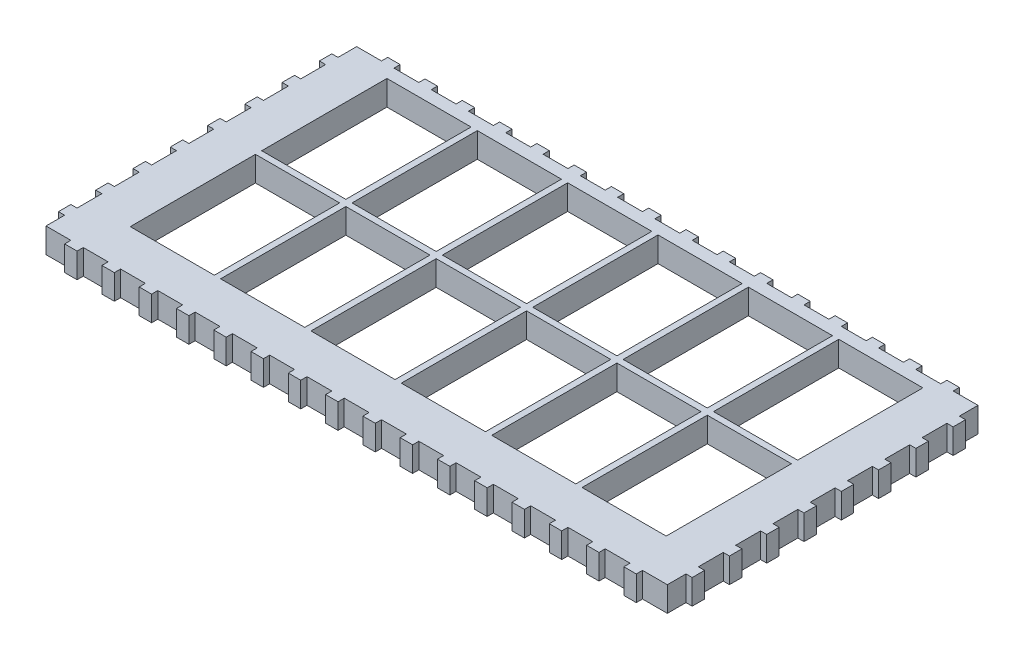
SolidWorks part; units mm, degrees
ref_plane "Front Plane" through (0, 0, 0) normal (0, 0, 1) x (1, 0, 0)
ref_plane "Top Plane" through (0, 0, 0) normal (0, 1, 0) x (1, 0, 0)
ref_plane "Right Plane" through (0, 0, 0) normal (1, 0, 0) x (0, 0, -1)
sketch "Sketch7" plane through (0, 0, 0) normal (0, 1, 0) x (1, 0, 0)
  line L0 (-95.525, 146.05) -> (-95.525, 18.05)
  line L1 (317.5, 158.75) -> (-317.5, 158.75)
  line L2 (317.5, 158.75) -> (317.5, -158.75)
  line L3 (317.5, -158.75) -> (-317.5, -158.75)
  line L4 (-317.5, 158.75) -> (-317.5, -158.75)
  line L5 (0, -158.75) -> (0, 158.75) construction
  line L6 (317.5, 0) -> (-317.5, 0) construction
  line L7 (-187.875, 146.05) -> (-273.875, 146.05)
  line L8 (-187.875, 146.05) -> (-187.875, 18.05)
  line L9 (-187.875, 18.05) -> (-273.875, 18.05)
  line L10 (-273.875, 146.05) -> (-273.875, 18.05)
  line L11 (-230.875, 18.05) -> (-230.875, 146.05) construction
  line L12 (-187.875, 82.05) -> (-273.875, 82.05) construction
  line L13 (-95.525, 18.05) -> (-181.525, 18.05)
  line L14 (-181.525, 146.05) -> (-181.525, 18.05)
  line L15 (-95.525, 146.05) -> (-181.525, 146.05)
  line L16 (-3.175, 146.05) -> (-3.175, 18.05)
  line L17 (-3.175, 18.05) -> (-89.175, 18.05)
  line L18 (-89.175, 146.05) -> (-89.175, 18.05)
  line L19 (-3.175, 146.05) -> (-89.175, 146.05)
  line L20 (89.175, 146.05) -> (89.175, 18.05)
  line L21 (89.175, 18.05) -> (3.175, 18.05)
  line L22 (3.175, 146.05) -> (3.175, 18.05)
  line L23 (89.175, 146.05) -> (3.175, 146.05)
  line L24 (181.525, 146.05) -> (181.525, 18.05)
  line L25 (181.525, 18.05) -> (95.525, 18.05)
  line L26 (95.525, 146.05) -> (95.525, 18.05)
  line L27 (181.525, 146.05) -> (95.525, 146.05)
  line L28 (273.875, 146.05) -> (273.875, 18.05)
  line L29 (273.875, 18.05) -> (187.875, 18.05)
  line L30 (187.875, 146.05) -> (187.875, 18.05)
  line L31 (273.875, 146.05) -> (187.875, 146.05)
  line L32 (-95.525, 11.7) -> (-95.525, -116.3)
  line L33 (-95.525, -116.3) -> (-181.525, -116.3)
  line L34 (-181.525, 11.7) -> (-181.525, -116.3)
  line L35 (-95.525, 11.7) -> (-181.525, 11.7)
  line L36 (-3.175, 11.7) -> (-3.175, -116.3)
  line L37 (-3.175, -116.3) -> (-89.175, -116.3)
  line L38 (-89.175, 11.7) -> (-89.175, -116.3)
  line L39 (-3.175, 11.7) -> (-89.175, 11.7)
  line L40 (89.175, 11.7) -> (89.175, -116.3)
  line L41 (89.175, -116.3) -> (3.175, -116.3)
  line L42 (3.175, 11.7) -> (3.175, -116.3)
  line L43 (89.175, 11.7) -> (3.175, 11.7)
  line L44 (181.525, 11.7) -> (181.525, -116.3)
  line L45 (181.525, -116.3) -> (95.525, -116.3)
  line L46 (95.525, 11.7) -> (95.525, -116.3)
  line L47 (181.525, 11.7) -> (95.525, 11.7)
  line L48 (273.875, 11.7) -> (273.875, -116.3)
  line L49 (273.875, -116.3) -> (187.875, -116.3)
  line L50 (187.875, 11.7) -> (187.875, -116.3)
  line L51 (273.875, 11.7) -> (187.875, 11.7)
  line L52 (-187.875, 11.7) -> (-187.875, -116.3)
  line L53 (-187.875, -116.3) -> (-273.875, -116.3)
  line L54 (-273.875, 11.7) -> (-273.875, -116.3)
  line L55 (-187.875, 11.7) -> (-273.875, 11.7)
  line L56 (-317.5, 146.05) -> (-273.875, 146.05) construction
  line L57 (273.875, 146.05) -> (317.5, 146.05) construction
  line L78 (-273.875, 146.05) -> (-317.5, 146.05) construction
  line L81 (-187.875, 18.05) -> (-187.875, 23.22) construction
  line L82 (-273.875, 146.05) -> (-273.875, 158.75) construction
  point P0 (0, 0)
  point P4 (-230.875, 82.05)
  dimension "D1" = 86
  dimension "D3" = 317.5
  dimension "D6" = 6.35
  dimension "D7" = 12.7
  dimension "D8" = 6.35
  dimension "D9" = 635
  dimension "D11" = 128
  dimension "D4" = 6
  dimension "D5" = 2
extrude "Boss-Extrude4" add sketch "Sketch7" along normal blind 25.4
sketch "Sketch8" plane through (0, 0, 0) normal (0, 1, 0) x (1, 0, 0)
  line L0 (-292.1, 158.75) -> (-292.1, 165.1)
  line L1 (-292.1, 165.1) -> (-279.4, 165.1)
  line L2 (-279.4, 165.1) -> (-279.4, 158.75)
  line L3 (317.5, 158.75) -> (-317.5, 158.75) construction
  line L4 (-292.1, 158.75) -> (-279.4, 158.75)
  line L29 (12.7, 165.1) -> (25.4, 165.1)
  line L58 (-317.5, 139.7) -> (-323.85, 139.7)
  line L59 (-317.5, 158.75) -> (-317.5, -158.75) construction
  line L60 (-323.85, 139.7) -> (-323.85, 127)
  line L61 (-323.85, 127) -> (-317.5, 127)
  line L62 (-317.5, 139.7) -> (-317.5, 127)
  line L63 (-323.85, 88.9) -> (-317.5, 88.9)
  line L64 (-317.5, 101.6) -> (-317.5, 88.9)
  line L65 (-317.5, 101.6) -> (-323.85, 101.6)
  line L66 (-323.85, 101.6) -> (-323.85, 88.9)
  line L67 (-323.85, 50.8) -> (-317.5, 50.8)
  line L68 (-317.5, 63.5) -> (-317.5, 50.8)
  line L69 (-317.5, 63.5) -> (-323.85, 63.5)
  line L70 (-323.85, 63.5) -> (-323.85, 50.8)
  line L71 (-323.85, 12.7) -> (-317.5, 12.7)
  line L72 (-317.5, 25.4) -> (-317.5, 12.7)
  line L73 (-317.5, 25.4) -> (-323.85, 25.4)
  line L74 (-323.85, 25.4) -> (-323.85, 12.7)
  line L75 (-323.85, -25.4) -> (-317.5, -25.4)
  line L76 (-317.5, -12.7) -> (-317.5, -25.4)
  line L77 (-317.5, -12.7) -> (-323.85, -12.7)
  line L78 (-323.85, -12.7) -> (-323.85, -25.4)
  line L95 (-323.85, -63.5) -> (-317.5, -63.5)
  line L120 (-317.5, -50.8) -> (-317.5, -63.5)
  line L121 (-317.5, -50.8) -> (-323.85, -50.8)
  line L122 (-323.85, -50.8) -> (-323.85, -63.5)
  line L123 (-323.85, -101.6) -> (-317.5, -101.6)
  line L124 (-317.5, -88.9) -> (-317.5, -101.6)
  line L125 (-317.5, -88.9) -> (-323.85, -88.9)
  line L126 (-323.85, -88.9) -> (-323.85, -101.6)
  line L127 (-323.85, -139.7) -> (-317.5, -139.7)
  line L128 (-317.5, -127) -> (-317.5, -139.7)
  line L129 (-317.5, -127) -> (-323.85, -127)
  line L130 (-323.85, -127) -> (-323.85, -139.7)
  line L131 (-317.5, -158.75) -> (317.5, -158.75) construction
  line L132 (-254, 165.1) -> (-241.3, 165.1)
  line L133 (-241.3, 165.1) -> (-241.3, 158.75)
  line L134 (-254, 158.75) -> (-241.3, 158.75)
  line L135 (-254, 158.75) -> (-254, 165.1)
  line L136 (-215.9, 165.1) -> (-203.2, 165.1)
  line L137 (-203.2, 165.1) -> (-203.2, 158.75)
  line L138 (-215.9, 158.75) -> (-203.2, 158.75)
  line L139 (-215.9, 158.75) -> (-215.9, 165.1)
  line L140 (-177.8, 165.1) -> (-165.1, 165.1)
  line L141 (-165.1, 165.1) -> (-165.1, 158.75)
  line L142 (-177.8, 158.75) -> (-165.1, 158.75)
  line L143 (-177.8, 158.75) -> (-177.8, 165.1)
  line L144 (-139.7, 165.1) -> (-127, 165.1)
  line L145 (-127, 165.1) -> (-127, 158.75)
  line L146 (-139.7, 158.75) -> (-127, 158.75)
  line L147 (-139.7, 158.75) -> (-139.7, 165.1)
  line L148 (-101.6, 165.1) -> (-88.9, 165.1)
  line L149 (-88.9, 165.1) -> (-88.9, 158.75)
  line L150 (-101.6, 158.75) -> (-88.9, 158.75)
  line L151 (-101.6, 158.75) -> (-101.6, 165.1)
  line L152 (-63.5, 165.1) -> (-50.8, 165.1)
  line L153 (-50.8, 165.1) -> (-50.8, 158.75)
  line L154 (-63.5, 158.75) -> (-50.8, 158.75)
  line L155 (-63.5, 158.75) -> (-63.5, 165.1)
  line L156 (-25.4, 165.1) -> (-12.7, 165.1)
  line L157 (-12.7, 165.1) -> (-12.7, 158.75)
  line L158 (-25.4, 158.75) -> (-12.7, 158.75)
  line L159 (-25.4, 158.75) -> (-25.4, 165.1)
  line L160 (-44.45, 139.7) -> (-50.8, 139.7) [skipped]
  line L161 (-50.8, 139.7) -> (-50.8, 127) [skipped]
  line L162 (-50.8, 127) -> (-44.45, 127) [skipped]
  line L163 (-44.45, 139.7) -> (-44.45, 127) [skipped]
  line L164 (-50.8, 88.9) -> (-44.45, 88.9) [skipped]
  line L165 (-44.45, 101.6) -> (-44.45, 88.9) [skipped]
  line L166 (-44.45, 101.6) -> (-50.8, 101.6) [skipped]
  line L167 (-50.8, 101.6) -> (-50.8, 88.9) [skipped]
  line L168 (-50.8, 50.8) -> (-44.45, 50.8) [skipped]
  line L169 (-44.45, 63.5) -> (-44.45, 50.8) [skipped]
  line L170 (-44.45, 63.5) -> (-50.8, 63.5) [skipped]
  line L171 (-50.8, 63.5) -> (-50.8, 50.8) [skipped]
  line L172 (-50.8, 12.7) -> (-44.45, 12.7) [skipped]
  line L173 (-44.45, 25.4) -> (-44.45, 12.7) [skipped]
  line L174 (-44.45, 25.4) -> (-50.8, 25.4) [skipped]
  line L175 (-50.8, 25.4) -> (-50.8, 12.7) [skipped]
  line L176 (-50.8, -25.4) -> (-44.45, -25.4) [skipped]
  line L177 (-44.45, -12.7) -> (-44.45, -25.4) [skipped]
  line L178 (-44.45, -12.7) -> (-50.8, -12.7) [skipped]
  line L179 (-50.8, -12.7) -> (-50.8, -25.4) [skipped]
  line L180 (25.4, 165.1) -> (25.4, 158.75)
  line L181 (12.7, 158.75) -> (25.4, 158.75)
  line L182 (12.7, 158.75) -> (12.7, 165.1)
  line L183 (50.8, 165.1) -> (63.5, 165.1)
  line L184 (63.5, 165.1) -> (63.5, 158.75)
  line L185 (50.8, 158.75) -> (63.5, 158.75)
  line L186 (50.8, 158.75) -> (50.8, 165.1)
  line L187 (88.9, 165.1) -> (101.6, 165.1)
  line L188 (101.6, 165.1) -> (101.6, 158.75)
  line L189 (88.9, 158.75) -> (101.6, 158.75)
  line L190 (88.9, 158.75) -> (88.9, 165.1)
  line L191 (127, 165.1) -> (139.7, 165.1)
  line L192 (139.7, 165.1) -> (139.7, 158.75)
  line L193 (127, 158.75) -> (139.7, 158.75)
  line L194 (127, 158.75) -> (127, 165.1)
  line L195 (165.1, 165.1) -> (177.8, 165.1)
  line L196 (177.8, 165.1) -> (177.8, 158.75)
  line L197 (165.1, 158.75) -> (177.8, 158.75)
  line L198 (165.1, 158.75) -> (165.1, 165.1)
  line L199 (203.2, 165.1) -> (215.9, 165.1)
  line L200 (215.9, 165.1) -> (215.9, 158.75)
  line L201 (203.2, 158.75) -> (215.9, 158.75)
  line L202 (203.2, 158.75) -> (203.2, 165.1)
  line L203 (241.3, 165.1) -> (254, 165.1)
  line L204 (254, 165.1) -> (254, 158.75)
  line L205 (241.3, 158.75) -> (254, 158.75)
  line L206 (241.3, 158.75) -> (241.3, 165.1)
  line L207 (279.4, 165.1) -> (292.1, 165.1)
  line L208 (292.1, 165.1) -> (292.1, 158.75)
  line L209 (279.4, 158.75) -> (292.1, 158.75)
  line L210 (279.4, 158.75) -> (279.4, 165.1)
  line L211 (317.5, -158.75) -> (317.5, 158.75) construction
  line L212 (-317.5, -158.75) -> (317.5, 158.75) construction
  line L213 (0, 0) -> (317.5, 0) construction
  line L214 (0, 0) -> (0, -158.75) construction
  line L215 (323.85, -127) -> (323.85, -139.7)
  line L216 (317.5, -127) -> (323.85, -127)
  line L217 (317.5, -127) -> (317.5, -139.7)
  line L218 (323.85, -139.7) -> (317.5, -139.7)
  line L219 (323.85, -88.9) -> (323.85, -101.6)
  line L220 (317.5, -88.9) -> (323.85, -88.9)
  line L221 (317.5, -88.9) -> (317.5, -101.6)
  line L222 (323.85, -101.6) -> (317.5, -101.6)
  line L223 (323.85, -50.8) -> (323.85, -63.5)
  line L224 (317.5, -50.8) -> (323.85, -50.8)
  line L225 (317.5, -50.8) -> (317.5, -63.5)
  line L226 (323.85, -63.5) -> (317.5, -63.5)
  line L227 (323.85, -12.7) -> (323.85, -25.4)
  line L228 (317.5, -12.7) -> (323.85, -12.7)
  line L229 (317.5, -12.7) -> (317.5, -25.4)
  line L230 (323.85, -25.4) -> (317.5, -25.4)
  line L231 (323.85, 25.4) -> (323.85, 12.7)
  line L232 (317.5, 25.4) -> (323.85, 25.4)
  line L233 (317.5, 25.4) -> (317.5, 12.7)
  line L234 (323.85, 12.7) -> (317.5, 12.7)
  line L235 (323.85, 63.5) -> (323.85, 50.8)
  line L236 (317.5, 63.5) -> (323.85, 63.5)
  line L237 (317.5, 63.5) -> (317.5, 50.8)
  line L238 (323.85, 50.8) -> (317.5, 50.8)
  line L239 (323.85, 101.6) -> (323.85, 88.9)
  line L240 (317.5, 101.6) -> (323.85, 101.6)
  line L241 (317.5, 101.6) -> (317.5, 88.9)
  line L242 (323.85, 88.9) -> (317.5, 88.9)
  line L243 (317.5, 139.7) -> (317.5, 127)
  line L244 (323.85, 127) -> (317.5, 127)
  line L245 (323.85, 139.7) -> (323.85, 127)
  line L246 (317.5, 139.7) -> (323.85, 139.7)
  line L247 (279.4, -158.75) -> (279.4, -165.1)
  line L248 (279.4, -158.75) -> (292.1, -158.75)
  line L249 (292.1, -165.1) -> (292.1, -158.75)
  line L250 (279.4, -165.1) -> (292.1, -165.1)
  line L251 (241.3, -158.75) -> (241.3, -165.1)
  line L252 (241.3, -158.75) -> (254, -158.75)
  line L253 (254, -165.1) -> (254, -158.75)
  line L254 (241.3, -165.1) -> (254, -165.1)
  line L255 (203.2, -158.75) -> (203.2, -165.1)
  line L256 (203.2, -158.75) -> (215.9, -158.75)
  line L257 (215.9, -165.1) -> (215.9, -158.75)
  line L258 (203.2, -165.1) -> (215.9, -165.1)
  line L259 (165.1, -158.75) -> (165.1, -165.1)
  line L260 (165.1, -158.75) -> (177.8, -158.75)
  line L261 (177.8, -165.1) -> (177.8, -158.75)
  line L262 (165.1, -165.1) -> (177.8, -165.1)
  line L263 (127, -158.75) -> (127, -165.1)
  line L264 (127, -158.75) -> (139.7, -158.75)
  line L265 (139.7, -165.1) -> (139.7, -158.75)
  line L266 (127, -165.1) -> (139.7, -165.1)
  line L267 (88.9, -158.75) -> (88.9, -165.1)
  line L268 (88.9, -158.75) -> (101.6, -158.75)
  line L269 (101.6, -165.1) -> (101.6, -158.75)
  line L270 (88.9, -165.1) -> (101.6, -165.1)
  line L271 (50.8, -158.75) -> (50.8, -165.1)
  line L272 (50.8, -158.75) -> (63.5, -158.75)
  line L273 (63.5, -165.1) -> (63.5, -158.75)
  line L274 (50.8, -165.1) -> (63.5, -165.1)
  line L275 (12.7, -158.75) -> (12.7, -165.1)
  line L276 (12.7, -158.75) -> (25.4, -158.75)
  line L277 (25.4, -165.1) -> (25.4, -158.75)
  line L278 (-25.4, -158.75) -> (-25.4, -165.1)
  line L279 (-25.4, -158.75) -> (-12.7, -158.75)
  line L280 (-12.7, -165.1) -> (-12.7, -158.75)
  line L281 (-25.4, -165.1) -> (-12.7, -165.1)
  line L282 (-63.5, -158.75) -> (-63.5, -165.1)
  line L283 (-63.5, -158.75) -> (-50.8, -158.75)
  line L284 (-50.8, -165.1) -> (-50.8, -158.75)
  line L285 (-63.5, -165.1) -> (-50.8, -165.1)
  line L286 (-101.6, -158.75) -> (-101.6, -165.1)
  line L287 (-101.6, -158.75) -> (-88.9, -158.75)
  line L288 (-88.9, -165.1) -> (-88.9, -158.75)
  line L289 (-101.6, -165.1) -> (-88.9, -165.1)
  line L290 (-139.7, -158.75) -> (-139.7, -165.1)
  line L291 (-139.7, -158.75) -> (-127, -158.75)
  line L292 (-127, -165.1) -> (-127, -158.75)
  line L293 (-139.7, -165.1) -> (-127, -165.1)
  line L294 (-177.8, -158.75) -> (-177.8, -165.1)
  line L295 (-177.8, -158.75) -> (-165.1, -158.75)
  line L296 (-165.1, -165.1) -> (-165.1, -158.75)
  line L297 (-177.8, -165.1) -> (-165.1, -165.1)
  line L298 (-215.9, -158.75) -> (-215.9, -165.1)
  line L299 (-215.9, -158.75) -> (-203.2, -158.75)
  line L300 (-203.2, -165.1) -> (-203.2, -158.75)
  line L301 (-215.9, -165.1) -> (-203.2, -165.1)
  line L302 (-254, -158.75) -> (-254, -165.1)
  line L303 (-254, -158.75) -> (-241.3, -158.75)
  line L304 (-241.3, -165.1) -> (-241.3, -158.75)
  line L305 (-254, -165.1) -> (-241.3, -165.1)
  line L306 (12.7, -165.1) -> (25.4, -165.1)
  line L307 (-292.1, -158.75) -> (-279.4, -158.75)
  line L308 (-279.4, -165.1) -> (-279.4, -158.75)
  line L309 (-292.1, -165.1) -> (-279.4, -165.1)
  line L310 (-292.1, -158.75) -> (-292.1, -165.1)
  dimension "D1" = 12.7
  dimension "D2" = 6.35
  dimension "D3" = 25.4
  dimension "D4" = 16
  dimension "D5" = 25.4
  dimension "D6" = 25.4
  dimension "D8" = 19.05
  dimension "D12" = 19.05
  dimension "D13" = 25.4
  dimension "D9" = 8
extrude "Boss-Extrude5" add sketch "Sketch8" along normal blind 25.4
